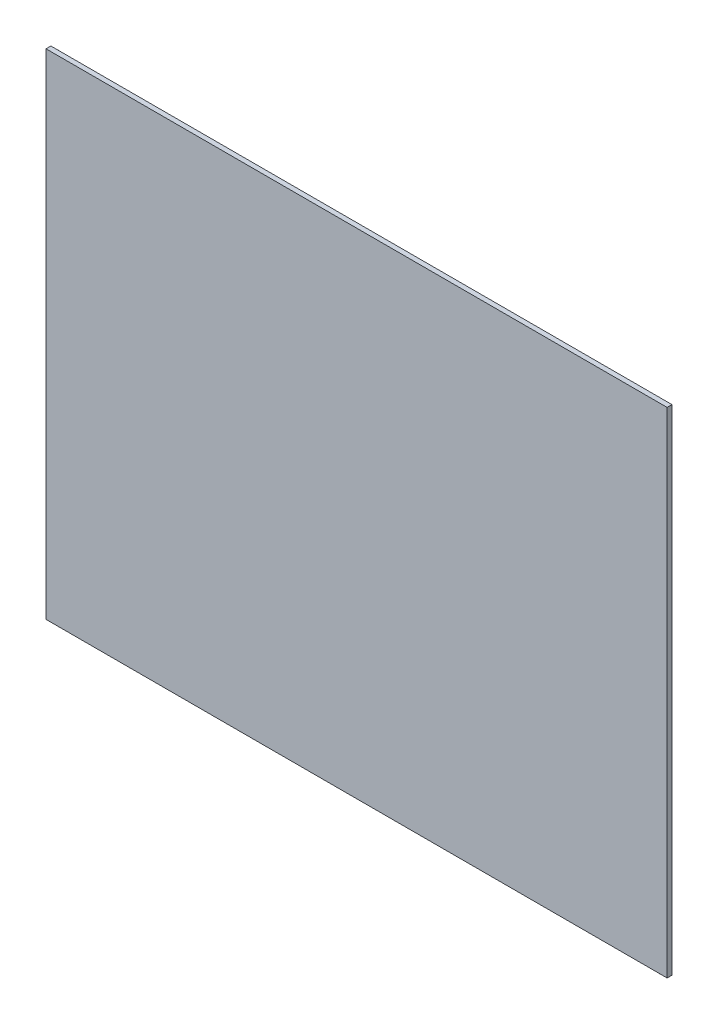
SolidWorks part; units mm, degrees
ref_plane "Plan de face" through (0, 0, 0) normal (0, 0, 1) x (1, 0, 0)
ref_plane "Plan de dessus" through (0, 0, 0) normal (0, 1, 0) x (1, 0, 0)
ref_plane "Plan de droite" through (0, 0, 0) normal (1, 0, 0) x (0, 0, -1)
sketch "Esquisse1" plane through (0, 0, 0) normal (0, 0, 1) x (1, 0, 0)
  line L1 (-416, -331) -> (416, -331)
  line L2 (-416, -331) -> (-416, 331)
  line L3 (-416, 331) -> (416, 331)
  line L4 (416, -331) -> (416, 331)
  line L5 (-416, -331) -> (416, 331) construction
  line L6 (-416, 331) -> (416, -331) construction
  point P0 (0, 0)
  dimension "D1" = 662
  dimension "D2" = 832
extrude "Boss.-Extru.1" add sketch "Esquisse1" along normal blind 6.5
